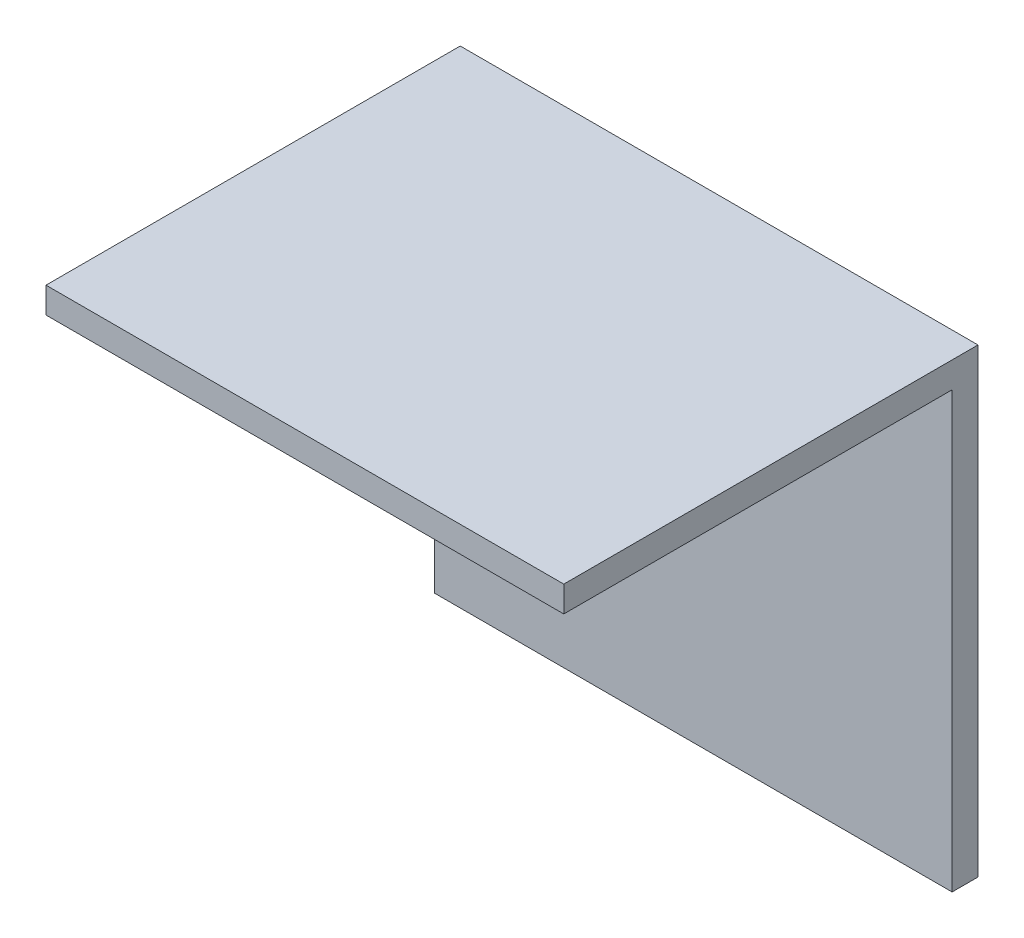
SolidWorks part; units mm, degrees
ref_plane "Plano frontal" through (0, 0, 0) normal (0, 0, 1) x (1, 0, 0)
ref_plane "Plano superior" through (0, 0, 0) normal (0, 1, 0) x (1, 0, 0)
ref_plane "Plano direito" through (0, 0, 0) normal (1, 0, 0) x (0, 0, -1)
sketch "Esboço1" plane through (0, 0, 0) normal (0, 0, 1) x (1, 0, 0)
  line L7 (-298.3526, -89) -> (-98.3526, -89)
  line L8 (-298.3526, -89) -> (-298.3526, 89)
  line L9 (-298.3526, 89) -> (-98.3526, 89)
  line L10 (-98.3526, -89) -> (-98.3526, 89)
  point P4 (-298.3526, 0)
  dimension "D1" = 178
  dimension "D2" = 200
extrude "Ressalto-extrusão1" add sketch "Esboço1" along normal blind 10
sketch "Esboço3" plane through (0, 0, 10) normal (0, 0, 1) x (1, 0, 0)
  line L0 (-98.3526, -89) -> (-98.3526, 89) construction
  line L1 (-298.3526, 89) -> (-98.3526, 89)
  line L2 (-298.3526, 89) -> (-298.3526, 79)
  line L3 (-298.3526, 79) -> (-98.3526, 79)
  line L4 (-98.3526, 89) -> (-98.3526, 79)
  dimension "D1" = 10
extrude "Ressalto-extrusão2" add sketch "Esboço3" along normal blind 150
sketch "Esboço4" plane through (0, 0, 10) normal (0, 0, 1) x (1, 0, 0)
  line L0 (-298.3526, -89) -> (-298.3526, -0.1112) construction
  line L1 (-298.3526, 79) -> (-298.3526, -89) construction
  line L2 (-298.3526, -0.1112) -> (-231.6856, -0.1112) construction
  circle A0 centre (-231.6856, -0.1112) radius 5
extrude "Corte-extrusão1" cut sketch "Esboço4" against normal through all both and the other way through all
